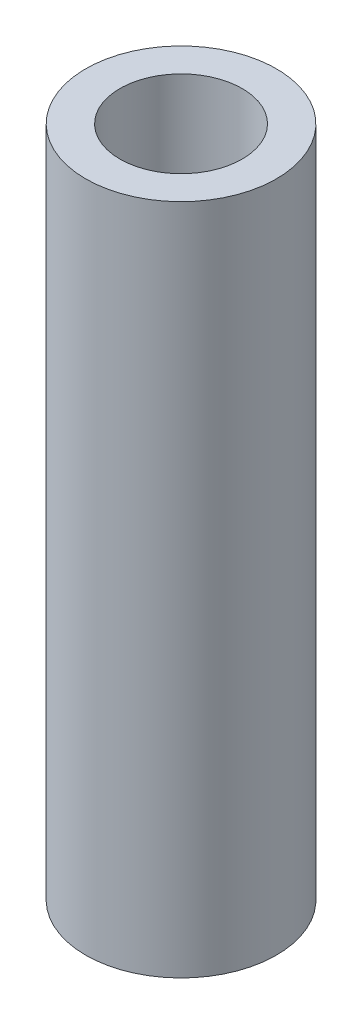
SolidWorks part; units mm, degrees
material "ABS"
ref_plane "Front Plane" through (0, 0, 0) normal (0, 0, 1) x (1, 0, 0)
ref_plane "Top Plane" through (0, 0, 0) normal (0, 1, 0) x (1, 0, 0)
ref_plane "Right Plane" through (0, 0, 0) normal (1, 0, 0) x (0, 0, -1)
sketch "Sketch1" plane through (0, 0, 0) normal (0, 1, 0) x (1, 0, 0)
  circle A0 centre (0, 0) radius 17.875
  circle A1 centre (0, 0) radius 27.875
  dimension "D1" = 35.75
  dimension "D2" = 55.75
extrude "Boss-Extrude1" add sketch "Sketch1" along normal blind 196.5
sketch "Sketch2" plane through (0, 0, 0) normal (1, 0, 0) x (0, 0, -1)
  line L0 (17.875, 196.5) -> (-17.875, 196.5) construction
  circle A0 centre (0, 131.8) radius 11.53
  circle A1 centre (0, 80.8) radius 11.53
  circle A2 centre (0, 29.8) radius 11.53
  dimension "D1" = 23.06
  dimension "D2" = 23.06
  dimension "D3" = 23.06
  dimension "D4" = 64.7
  dimension "D5" = 51
  dimension "D6" = 51
extrude "Cut-Extrude1" cut sketch "Sketch2" against normal through all
